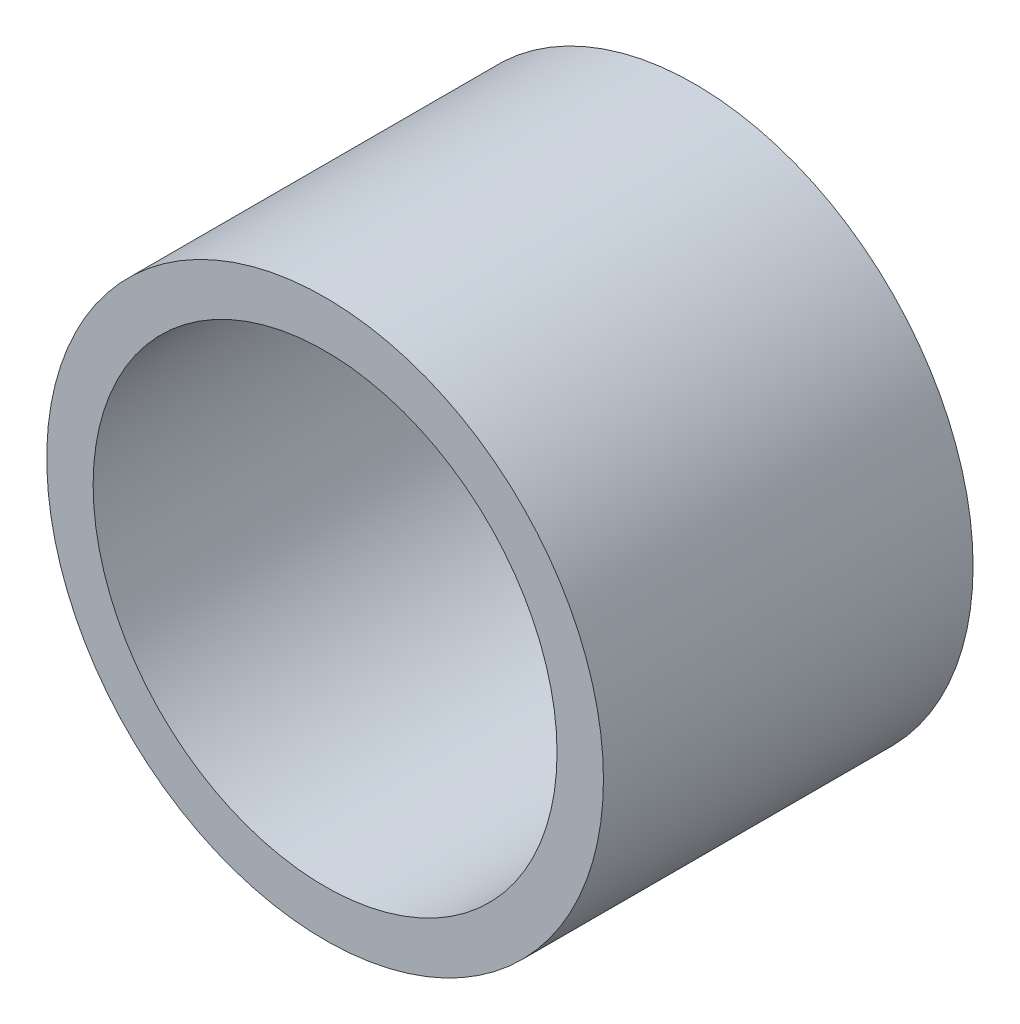
SolidWorks part; units mm, degrees
material "6061-T6 (SS)"
ref_plane "Front Plane" through (0, 0, 0) normal (0, 0, 1) x (1, 0, 0)
ref_plane "Top Plane" through (0, 0, 0) normal (0, 1, 0) x (1, 0, 0)
ref_plane "Right Plane" through (0, 0, 0) normal (1, 0, 0) x (0, 0, -1)
sketch "Sketch1" plane through (0, 0, 0) normal (0, 0, 1) x (1, 0, 0)
  line L1 (7.3323, 0) -> (3.6662, 6.35) construction
  line L2 (3.6662, 6.35) -> (-3.6662, 6.35) construction
  line L3 (-3.6662, 6.35) -> (-7.3323, 0) construction
  line L4 (-7.3323, 0) -> (-3.6662, -6.35) construction
  line L5 (-3.6662, -6.35) -> (3.6662, -6.35) construction
  line L6 (3.6662, -6.35) -> (7.3323, 0) construction
  circle A0 centre (0, 0) radius 6.35 construction
  circle A1 centre (0, 0) radius 7.9375
  circle A2 centre (0, 0) radius 9.525
  dimension "D2" = 15.875
  dimension "D3" = 19.05
  dimension "D1" = 12.7
extrude "Boss-Extrude1" add sketch "Sketch1" along normal blind 12.6492
